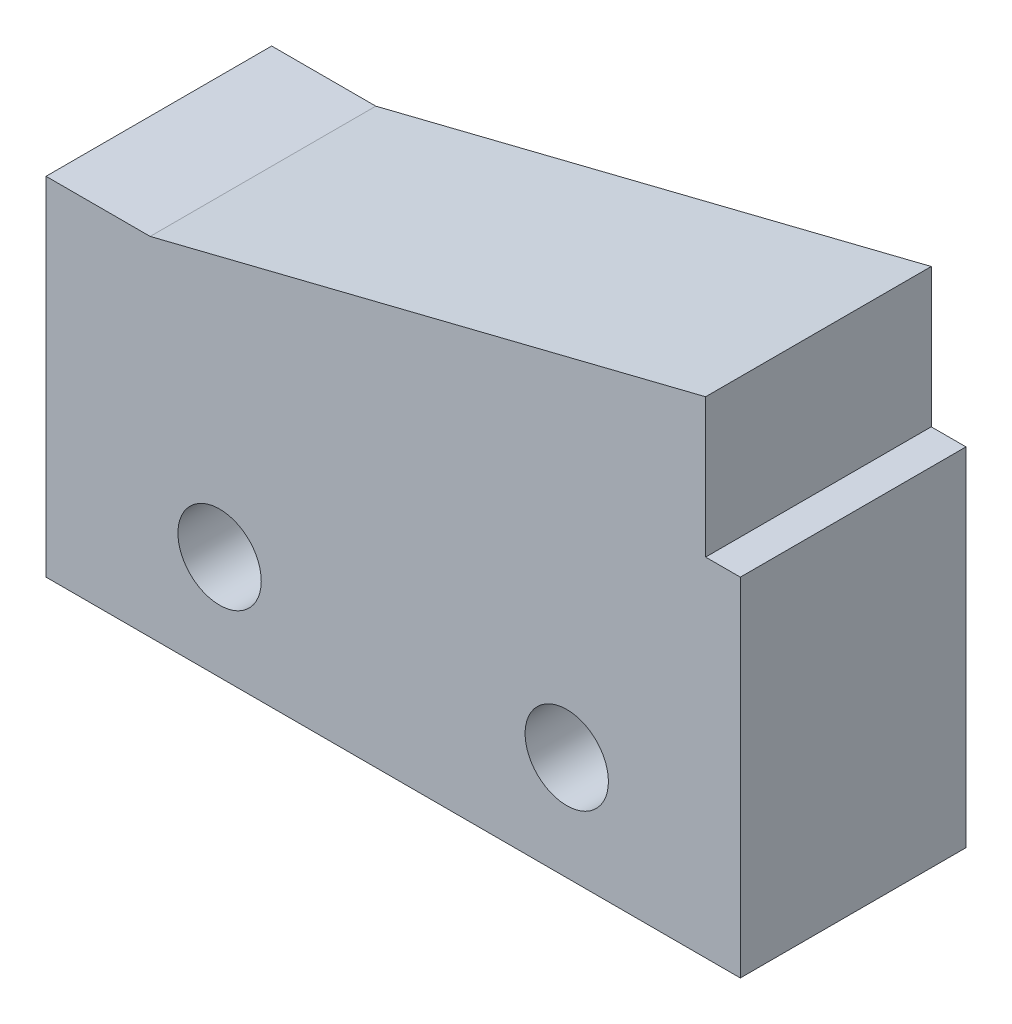
SolidWorks part; units mm, degrees
ref_plane "Front Plane" through (0, 0, 0) normal (0, 0, 1) x (1, 0, 0)
ref_plane "Top Plane" through (0, 0, 0) normal (0, 1, 0) x (1, 0, 0)
ref_plane "Right Plane" through (0, 0, 0) normal (1, 0, 0) x (0, 0, -1)
sketch "Sketch1" plane through (0, 0, 0) normal (0, 0, 1) x (1, 0, 0)
  line L0 (3, 10) -> (19, 14)
  line L1 (0, 0) -> (20, 0)
  line L2 (0, 0) -> (0, 10)
  line L3 (0, 10) -> (20, 10)
  line L4 (20, 0) -> (20, 10)
  line L5 (19, 14) -> (19, 10)
  dimension "D1" = 20
  dimension "D2" = 10
  dimension "D3" = 4
  dimension "D4" = 3
  dimension "D5" = 1
extrude "Boss-Extrude1" add sketch "Sketch1" along normal blind 6.5 contours L5 L0 L3 | L1 L4 L3 L2
hole_wizard "M2 Clearance Hole1" positions "Sketch2" profile "Sketch3" hole size "M2" standard "ANSI Metric" end condition up to next
sketch "Sketch2" plane through (0, 0, 6.5) normal (0, 0, 1) x (1, 0, 0)
  line L3 (0, 0) -> (0, 10) construction
  line L4 (20, 0) -> (20, 10) construction
  line L5 (0, 0) -> (20, 0) construction
  point P0 (5, 3)
  point P2 (15, 3)
  dimension "D1" = 5
  dimension "D2" = 5
  dimension "D3" = 3
  dimension "D4" = 3
sketch "Sketch3" plane through (5, 3, 6.5) normal (1, 0, 0) x (0, -1, 0)
  line L0 (0, 0) -> (0, 6.5)
  line L1 (0, 6.5) -> (1.2, 6.5)
  line L2 (1.2, 6.5) -> (1.2, 0)
  line L5 (1.2, 0) -> (0, 0)
  line L11 (0, -6.35) -> (0, 107.95) construction
  dimension "Thru Hole Dia." = 2.4
  dimension "Thru Hole Depth" = 6.5
